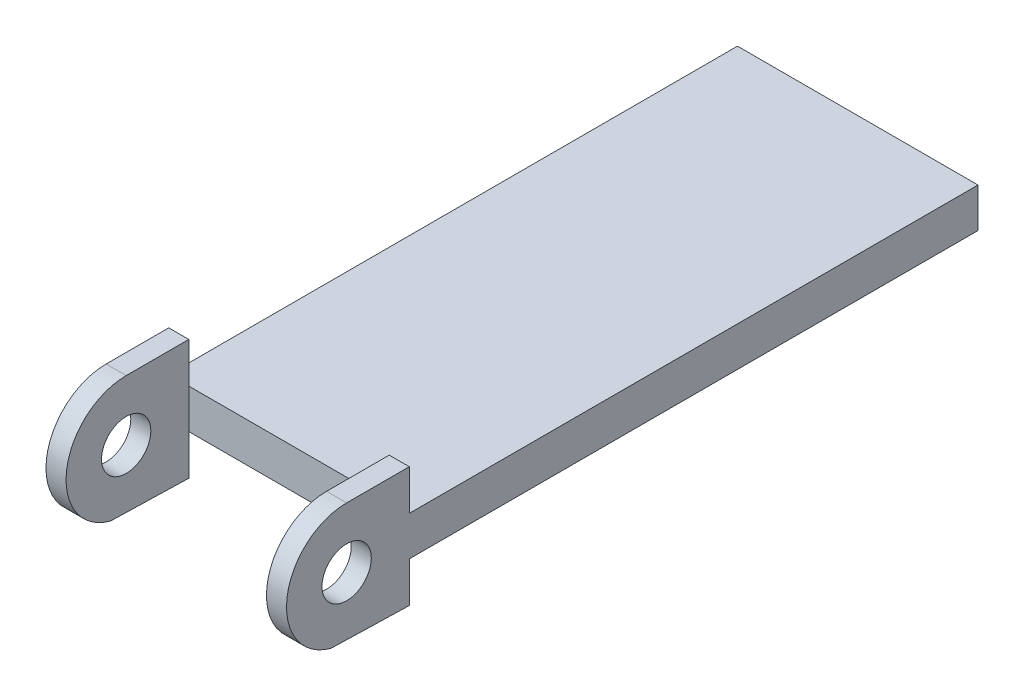
SolidWorks part; units mm, degrees
ref_plane "Front Plane" through (0, 0, 0) normal (0, 0, 1) x (1, 0, 0)
ref_plane "Top Plane" through (0, 0, 0) normal (0, 1, 0) x (1, 0, 0)
ref_plane "Right Plane" through (0, 0, 0) normal (1, 0, 0) x (0, 0, -1)
sketch "Sketch1" plane through (0, 0, 0) normal (0, 1, 0) x (1, 0, 0)
  line L1 (-6.096, 15.367) -> (6.096, 15.367)
  line L2 (-6.096, 15.367) -> (-6.096, -15.367)
  line L3 (-6.096, -15.367) -> (6.096, -15.367)
  line L4 (6.096, 15.367) -> (6.096, -15.367)
  line L5 (-6.096, 15.367) -> (6.096, -15.367) construction
  line L6 (-6.096, -15.367) -> (6.096, 15.367) construction
  point P0 (0, 0)
  dimension "D1" = 12.192
  dimension "D2" = 30.734
extrude "Boss-Extrude1" add sketch "Sketch1" along normal blind 2
sketch "Sketch2" plane through (6.096, 0, 0) normal (1, 0, 0) x (0, 0, -1)
  line L0 (-15.367, 1) -> (-16.637, 1) construction
  line L1 (-15.367, 2) -> (-15.367, 0) construction
  line L2 (-16.637, 4.048) -> (-13.462, 4.048)
  line L3 (-13.462, 4.048) -> (-13.462, -2.048)
  line L4 (-13.462, -2.048) -> (-17.4352, -1.9416)
  circle A0 centre (-16.637, 1) radius 3.048
  dimension "D1" = 1.778
  dimension "D2" = 1.27
  dimension "D3" = 3.175
extrude "Boss-Extrude2" add sketch "Sketch2" against normal up to surface (12.192 mm away)
sketch "Sketch3" plane through (6.096, 0, 0) normal (1, 0, 0) x (0, 0, -1)
  circle A0 centre (-16.637, 1) radius 1.25
  dimension "D1" = 2.5
extrude "Cut-Extrude1" cut sketch "Sketch3" against normal through all
sketch "Sketch4" plane through (0, 2, 0) normal (0, 1, 0) x (1, 0, 0)
  line L0 (-5.08, -13.462) -> (-5.08, -19.685)
  line L1 (6.096, -13.462) -> (6.096, 15.367) construction
  line L2 (-6.096, -19.685) -> (6.096, -19.685) construction
  line L3 (-5.08, -19.685) -> (5.08, -19.685)
  line L4 (5.08, -19.685) -> (5.08, -13.462)
  line L5 (5.08, -13.462) -> (-5.08, -13.462)
  line L6 (-6.096, -16.637) -> (-6.096, -19.685) construction
  line L9 (-6.096, -13.462) -> (6.096, -13.462) construction
  point P10 (-5.08, -14.097)
  dimension "D1" = 1.016
  dimension "D2" = 1.016
extrude "Cut-Extrude2" cut sketch "Sketch4" against normal through all both and the other way through all
